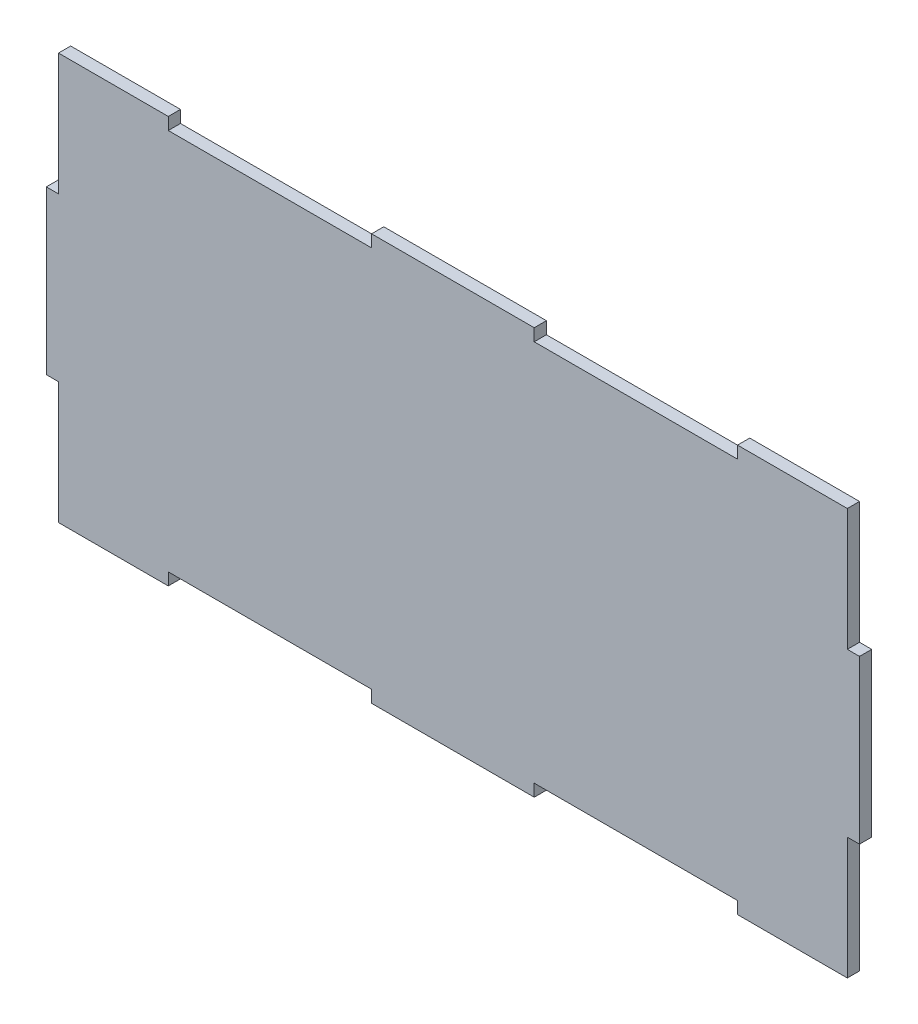
SolidWorks part; units mm, degrees
ref_plane "Plan de face" through (0, 0, 0) normal (0, 0, 1) x (1, 0, 0)
ref_plane "Plan de dessus" through (0, 0, 0) normal (0, 1, 0) x (1, 0, 0)
ref_plane "Plan de droite" through (0, 0, 0) normal (1, 0, 0) x (0, 0, -1)
sketch "Esquisse2" plane through (0, 0, 0) normal (0, 0, 1) x (1, 0, 0)
  line L0 (26.9639, 9.1911) -> (66.9639, 9.1911)
  line L1 (-50.0361, 9.1911) -> (-23.0361, 9.1911)
  line L2 (-53.0361, -20.8089) -> (-53.0361, -60.8089)
  line L3 (-50.0361, -90.8089) -> (-23.0361, -90.8089)
  line L4 (146.9639, -20.8089) -> (146.9639, -60.8089)
  line L5 (116.9639, 9.1911) -> (143.9639, 9.1911)
  line L6 (-23.0361, 9.1911) -> (-23.0361, 6.1911)
  line L7 (-23.0361, 6.1911) -> (26.9639, 6.1911)
  line L8 (26.9639, 9.1911) -> (26.9639, 6.1911)
  line L9 (116.9639, -90.8089) -> (143.9639, -90.8089)
  line L10 (66.9639, 9.1911) -> (66.9639, 6.1911)
  line L11 (66.9639, 6.1911) -> (116.9639, 6.1911)
  line L12 (116.9639, 9.1911) -> (116.9639, 6.1911)
  line L14 (-23.0361, -90.8089) -> (-23.0361, -87.8089)
  line L15 (-23.0361, -87.8089) -> (26.9639, -87.8089)
  line L16 (26.9639, -90.8089) -> (26.9639, -87.8089)
  line L17 (26.9639, -90.8089) -> (66.9639, -90.8089)
  line L18 (66.9639, -90.8089) -> (66.9639, -87.8089)
  line L19 (66.9639, -87.8089) -> (116.9639, -87.8089)
  line L20 (116.9639, -90.8089) -> (116.9639, -87.8089)
  line L22 (-50.0361, 9.1911) -> (-50.0361, -20.8089)
  line L23 (-50.0361, -20.8089) -> (-53.0361, -20.8089)
  line L25 (-53.0361, -60.8089) -> (-50.0361, -60.8089)
  line L28 (-50.0361, -60.8089) -> (-50.0361, -90.8089)
  line L29 (146.9639, -60.8089) -> (143.9639, -60.8089)
  line L32 (143.9639, -60.8089) -> (143.9639, -90.8089)
  line L34 (143.9639, 9.1911) -> (143.9639, -20.8089)
  line L35 (143.9639, -20.8089) -> (146.9639, -20.8089)
  dimension "D2" = 200
  dimension "D4" = 3
  dimension "D5" = 50
  dimension "D6" = 40
  dimension "D7" = 30
  dimension "D8" = 30
  dimension "D11" = 100
extrude "Boss.-Extru.1" add sketch "Esquisse2" along normal blind 3
